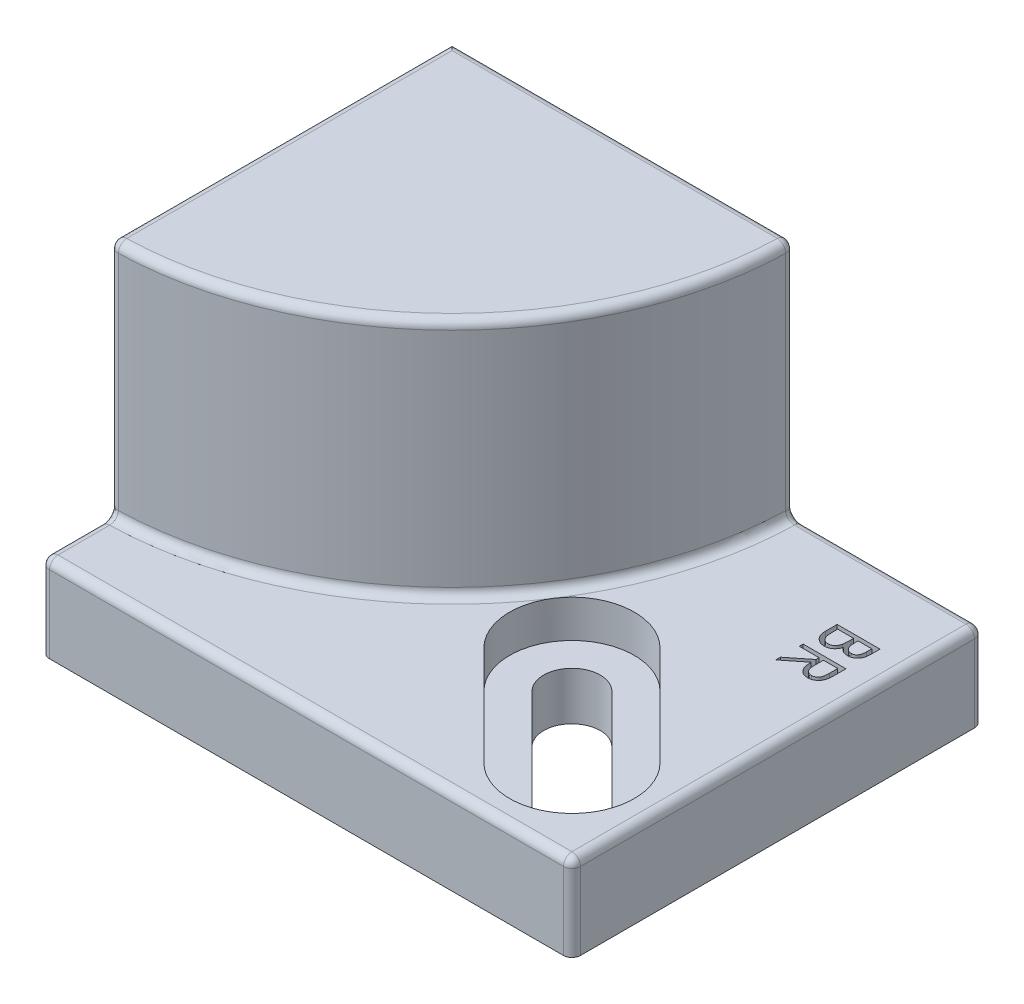
SolidWorks part; units mm, degrees
other "Markup1"
sketch "Sketch1" plane through (0, 0, 0) normal (0.5774, 0.5773, 0.5774) x (0.7071, 0, -0.7071)
sketch "Sketch2" plane through (0, 0, 0) normal (0.5774, 0.5773, 0.5774) x (0.7071, 0, -0.7071)
ref_plane "Front (z)" through (0, 0, 0) normal (0, 0, 1) x (1, 0, 0)
ref_plane "Top (y)" through (0, 0, 0) normal (0, 1, 0) x (1, 0, 0)
ref_plane "Right (x)" through (0, 0, 0) normal (1, 0, 0) x (0, 0, -1)
sketch "Sketch3" plane through (0, 0, 0) normal (0, 1, 0) x (1, 0, 0)
  line L1 (-31, -24) -> (31, -24)
  line L2 (-31, -24) -> (-31, 24)
  line L3 (-31, 24) -> (31, 24)
  line L4 (31, -24) -> (31, 24)
  line L5 (-31, -24) -> (31, 24) construction
  line L6 (-31, 24) -> (31, -24) construction
  point P0 (0, 0)
  dimension "D1" = 62
  dimension "D2" = 48
extrude "Boss-Extrude1" add sketch "Sketch3" along normal blind 10
hole_wizard "CBORE for M6 Hex Head Bolt1" positions "Sketch4" profile "Sketch5" counterbore size "M6" standard "ANSI Metric" end condition through all
sketch "Sketch4" plane through (0, 10, 0) normal (0, 1, 0) x (1, 0, 0)
  line L0 (-31, -24) -> (31, -24) construction
  line L1 (31, -24) -> (31, 24) construction
  point P0 (21, -14)
  dimension "D1" = 10
  dimension "D2" = 10
sketch "Sketch5" plane through (21, 10, 14) normal (1, 0, 0) x (0, 0, 1)
  line L0 (0, 0) -> (0, 10)
  line L1 (0, 10) -> (3.3, 10)
  line L3 (3.3, 10) -> (3.3, 4.38)
  line L4 (3.3, 4.38) -> (7.275, 4.38)
  line L5 (7.275, 4.38) -> (7.275, 0)
  line L7 (7.275, 0) -> (0, 0)
  line L11 (0, -6.35) -> (0, 107.95) construction
  dimension "Thru Hole Dia." = 6.6
  dimension "Thru Hole Depth" = 10
  dimension "C'Bore Dia." = 14.55
  dimension "C'Bore Depth" = 4.38
sketch "Sketch8" plane through (0, 10, 0) normal (0, 1, 0) x (1, 0, 0)
  line L0 (9, 24) -> (-1, 24)
  line L1 (-31, -6) -> (-31, -16)
  arc A0 (-31, -6) -> (-1, 24) centre (-31, 24) ccw
  arc A1 (-31, -16) -> (9, 24) centre (-31, 24) ccw
  circle A3 centre (-31, 24) radius 40 construction
  circle A4 centre (-31, 24) radius 30 construction
  point P4 (3.6891, 33.7712)
  point P9 (-5, 25)
  dimension "D1" = 60
  dimension "D3" = 48
  dimension "D4" = 62
  dimension "D2" = 10
extrude "Boss-Extrude3" add sketch "Sketch8" along normal blind 18
sketch "Sketch9" plane through (0, 28, 0) normal (0, 1, 0) x (1, 0, 0)
  line L0 (9, 24) -> (-31, 24)
  line L1 (-31, 24) -> (-31, -16)
  arc A0 (-31, -16) -> (9, 24) centre (-31, 24) ccw construction
  arc A1 (-31, -16) -> (9, 24) centre (-31, 24) ccw
extrude "Boss-Extrude4" add sketch "Sketch9" along normal blind 10
sketch "Sketch10" plane through (0, 10, 0) normal (0, 1, 0) x (1, 0, 0)
  line L2 (9, 24) -> (-31, 24) construction
  line L3 (-31, 24) -> (-31, -16) construction
  circle A0 centre (-18.5, 11.5) radius 3
  dimension "D1" = 6
  dimension "D2" = 12.5
  dimension "D3" = 12.5
extrude "Cut-Extrude2" cut sketch "Sketch10" against normal blind 6
fillet "Fillet1" radius 1 21 edges at (-16, 28, -24) (-16, 10, -24) (-31, 28, -9) (-31, 10, -9) (9, 24, -24) (-31, 24, 16) (-1, 19, -24) (-9.7868, 28, -2.7868) (-31, 19, 6) (-9.7868, 10, -2.7868) (-31, 38, -4) (-2.7157, 38, 4.2843) (-11, 38, -24) (20, 10, -24) (31, 5, -24) (31, 10, 0) (31, 5, 24) (-31, 5, 24) (0, 10, 24) (-31, 10, 20) (-2.7157, 10, 4.2843)
sketch "Sketch12" plane through (0, 10, 0) normal (0, 1, 0) x (1, 0, 0)
  line L0 (-30, 23) -> (-3.4228, -3.5772) construction
  line L1 (21, -14) -> (-14.4877, 21.4877) construction
  line L3 (15.8558, -19.1442) -> (4.2659, -7.5543)
  line L4 (26.1442, -8.8558) -> (14.5543, 2.7341)
  line L7 (-30, 23) -> (-31, 24) construction
  arc A1 (15.8558, -19.1442) -> (26.1442, -8.8558) centre (21, -14) ccw
  arc A2 (14.5543, 2.7341) -> (4.2659, -7.5543) centre (9.4101, -2.4101) ccw
  circle A3 centre (21, -14) radius 7.275 construction
  circle A5 centre (21, -14) radius 7.275 construction
  arc A6 (-30, -16.9878) -> (9.9878, 23) centre (-31, 24) ccw construction
  arc A8 (-30, -14.9872) -> (7.9872, 23) centre (-31, 24) ccw construction
extrude "Cut-Extrude3" cut sketch "Sketch12" against normal up to surface (4.38 mm away) up to face at (21, 5.62, 17.3)
sketch "Sketch13" plane through (0, 5.62, 0) normal (0, 1, 0) x (1, 0, 0)
  line L0 (4.2659, -7.5543) -> (14.5543, 2.7341) construction
  line L1 (7.0767, -4.7436) -> (18.6665, -16.3335)
  line L2 (11.7436, -0.0767) -> (23.3335, -11.6665)
  arc A0 (11.7436, -0.0767) -> (7.0767, -4.7436) centre (9.4101, -2.4101) ccw
  circle A1 centre (21, -14) radius 3.3 construction
  arc A3 (18.6665, -16.3335) -> (23.3335, -11.6665) centre (21, -14) ccw
extrude "Cut-Extrude4" cut sketch "Sketch13" against normal through all
sketch "Sketch14" plane through (0, 10, 0) normal (0, 1, 0) x (1, 0, 0)
  line L0 (22.5082, 0) -> (22.5082, 24) construction
  line L2 (9.9878, 24) -> (30, 24) construction
  text T0 "BR" font "Century Gothic" height 5
extrude "Cut-Extrude5" cut sketch "Sketch14" against normal blind 2
